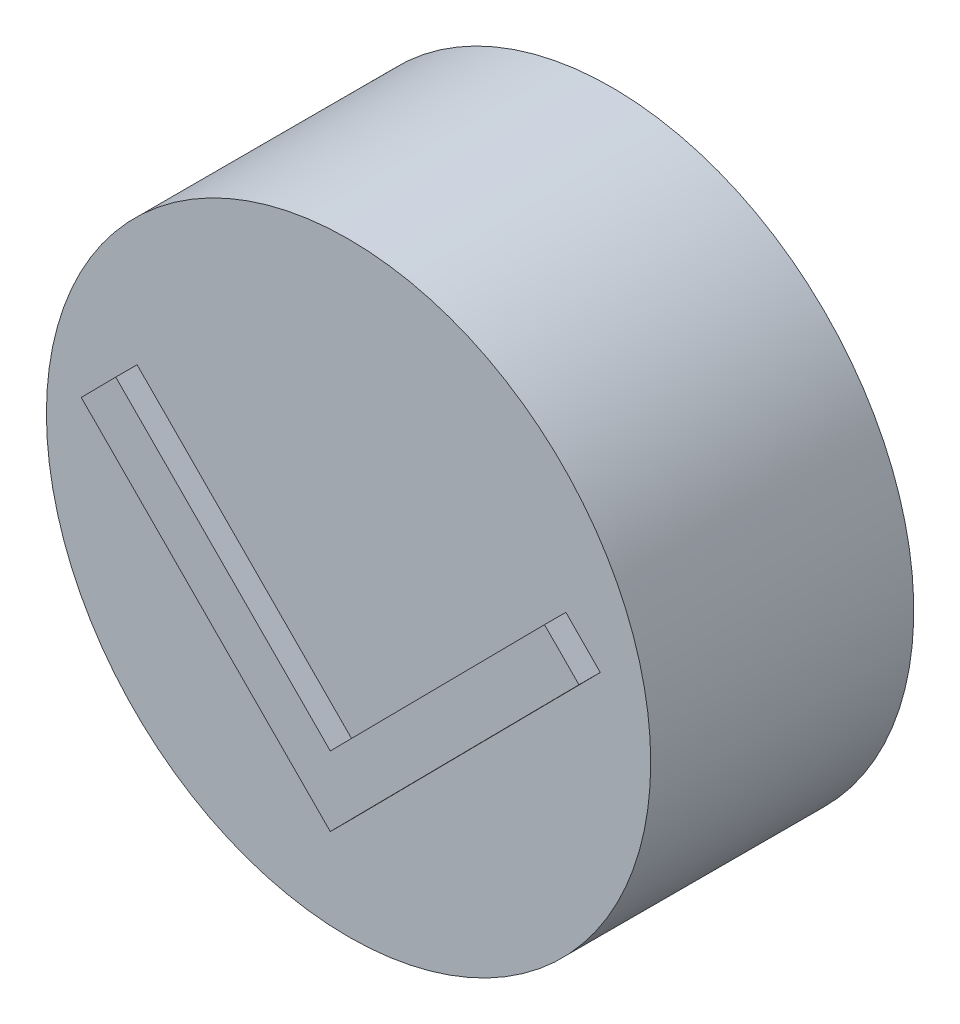
SolidWorks part; units mm, degrees
ref_plane "Front Plane" through (0, 0, 0) normal (0, 0, 1) x (1, 0, 0)
ref_plane "Top Plane" through (0, 0, 0) normal (0, 1, 0) x (1, 0, 0)
ref_plane "Right Plane" through (0, 0, 0) normal (1, 0, 0) x (0, 0, -1)
sketch "Sketch1" plane through (0, 0, 0) normal (0, 0, 1) x (1, 0, 0)
  circle A0 centre (0, 0) radius 8.5
  dimension "D1" = 17
extrude "Boss-Extrude1" add sketch "Sketch1" along normal blind 4.4
sketch "Sketch2" plane through (0, 0, 4.4) normal (0, 0, 1) x (1, 0, 0)
  line L19 (8.6958, 8.4084) -> (-2.0845, 8.4084) construction
  text T0 "T" font "Wingdings 3" height 14
  point P0 (8.6958, 8.4084)
  point P7 (3.2424, 1.1561)
  point P8 (6.4099, 5.3898)
  point P9 (0, 0)
  point P10 (7.712, 5.2328)
  point P11 (0, 0)
  point P12 (0, 0)
sketch "Sketch3" plane through (0, 0, 0) normal (0, 0, -1) x (-1, 0, 0)
  circle A0 centre (0, 0) radius 5.8
  dimension "D1" = 11.6
extrude "Cut-Extrude1" cut sketch "Sketch3" against normal blind 4
sketch "Sketch4" plane through (0, 0, 0) normal (0, 0, -1) x (-1, 0, 0)
  circle A1 centre (0, 0) radius 8.5
  circle A2 centre (0, 0) radius 8.5
  circle A4 centre (0, 0) radius 7.5
  dimension "D2" = 1
  dimension "D1" = 0
extrude "Boss-Extrude3" add sketch "Sketch4" along normal blind 3
sketch "Sketch6" plane through (0, 0, 0) normal (0, 1, 0) x (1, 0, 0)
  line L6 (7.5, 0) -> (5.8, -1.7)
  line L7 (5.8, -1.7) -> (5.8, 0)
  line L8 (5.8, 0) -> (7.5, 0)
  line L9 (7.5, 0) -> (-7.5, 0) construction
  line L10 (5.8, 0) -> (-5.8, 0) construction
  dimension "D1" = 45
ref_axis "Axis1" through (0, 0, -5.5) along (0, 0, 1)
revolve "Cut-Revolve1" cut sketch "Sketch6" angle 360 about axis through (0, 0, -5.5) along (0, 0, 1)
extrude "Boss-Extrude4" add sketch "Sketch2" along normal blind 0.6
